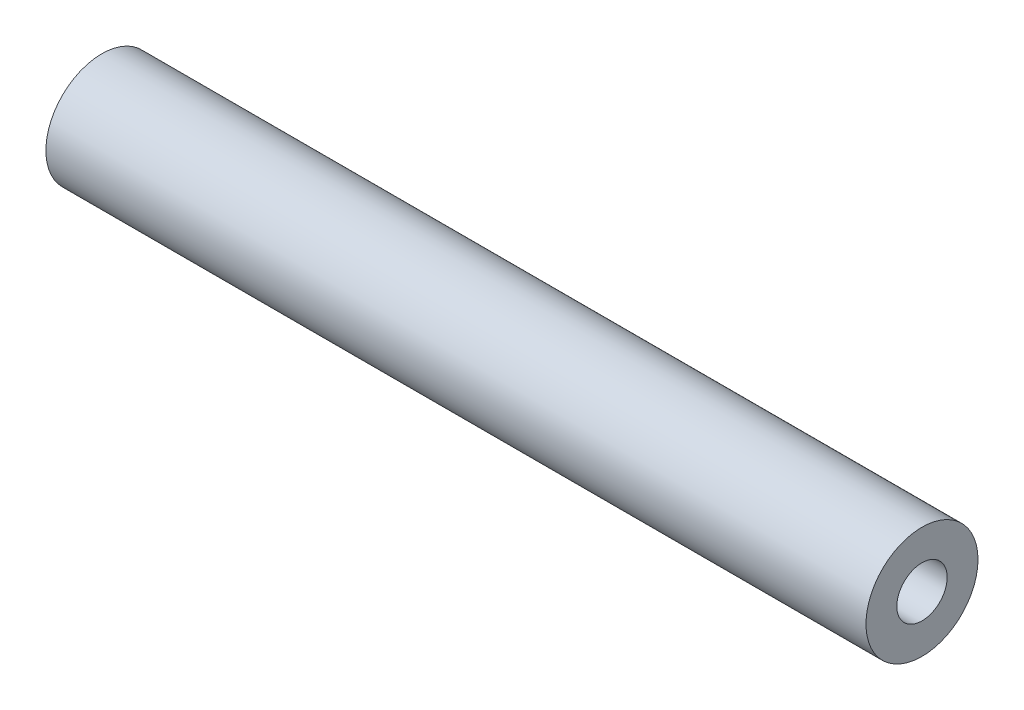
SolidWorks part; units mm, degrees
ref_plane "前视基准面" through (0, 0, 0) normal (0, 0, 1) x (1, 0, 0)
ref_plane "上视基准面" through (0, 0, 0) normal (0, 1, 0) x (1, 0, 0)
ref_plane "右视基准面" through (0, 0, 0) normal (1, 0, 0) x (0, 0, -1)
other "Configuration Table"
sketch "草图3" plane through (0, 0, 0) normal (1, 0, 0) x (0, 0, -1)
  circle A0 centre (0, 0) radius 2
  circle A1 centre (0, 0) radius 4.45
  dimension "D1" = 8.9
  dimension "D2" = 4
extrude "凸台-拉伸1" add sketch "草图3" along normal blind 65.16
